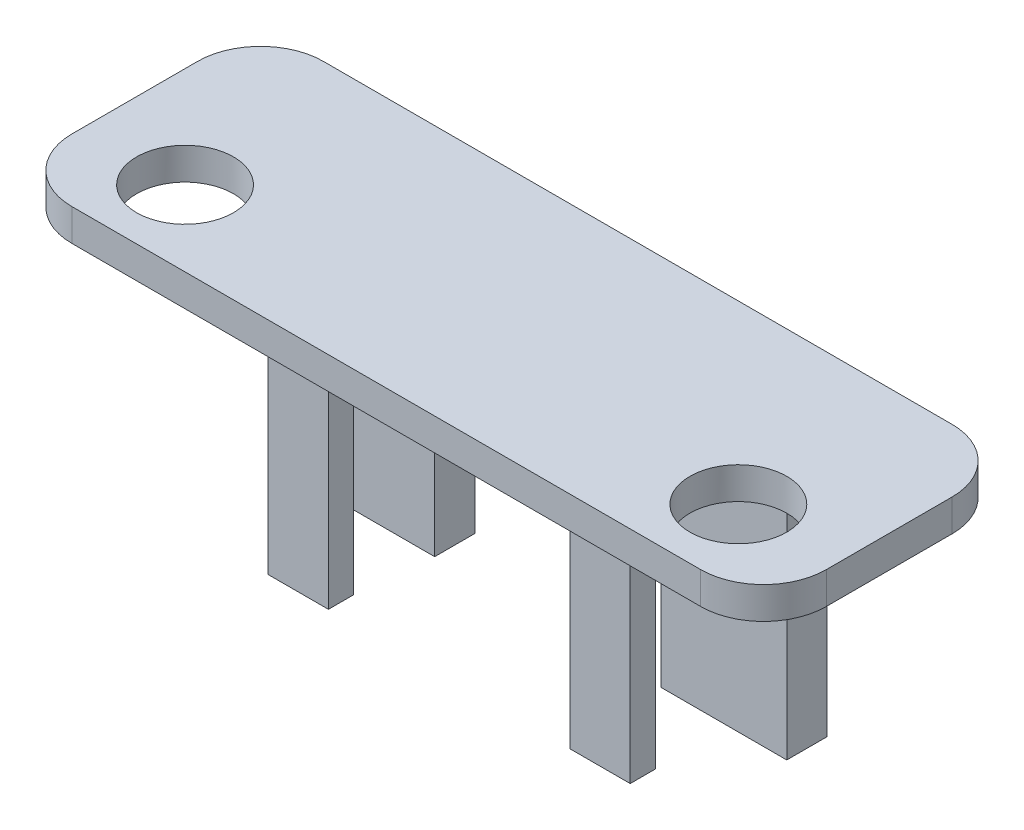
SolidWorks part; units mm, degrees
ref_plane "Front Plane" through (0, 0, 0) normal (0, 0, 1) x (1, 0, 0)
ref_plane "Top Plane" through (0, 0, 0) normal (0, 1, 0) x (1, 0, 0)
ref_plane "Right Plane" through (0, 0, 0) normal (1, 0, 0) x (0, 0, -1)
sketch "Sketch1" plane through (0, 0, 0) normal (0, 1, 0) x (1, 0, 0)
  line L1 (-30, -10) -> (30, -10)
  line L2 (-30, -10) -> (-30, 10)
  line L3 (-30, 10) -> (30, 10)
  line L4 (30, -10) -> (30, 10)
  line L5 (-30, -10) -> (30, 10) construction
  line L6 (-30, 10) -> (30, -10) construction
  point P0 (0, 0)
  dimension "D1" = 20
  dimension "D2" = 60
extrude "Boss-Extrude1" add sketch "Sketch1" along normal blind 2.54
sketch "Sketch2" plane through (0, 2.54, 0) normal (0, 1, 0) x (1, 0, 0)
  line L0 (-25.85, -4) -> (-18.15, -4) construction
  line L3 (0, 0) -> (0, 10) construction
  line L4 (30, 10) -> (-30, 10) construction
  line L5 (18.15, -4) -> (25.85, -4) construction
  line L6 (-30, -10) -> (30, -10) construction
  circle A0 centre (-22, -4) radius 3.85
  circle A1 centre (22, -4) radius 3.85
  dimension "D1" = 7.7
  dimension "D2" = 7.7
  dimension "D5" = 6
  dimension "D3" = 44
  dimension "D4" = 22
extrude "Eyeshaft holes" cut sketch "Sketch2" against normal blind 10
sketch "Sketch3" plane through (0, 0, -10) normal (0, 0, -1) x (-1, 0, 0)
  line L0 (-30, 2.54) -> (30, 2.54) construction
  line L1 (-13.5, 2.54) -> (-19.3221, 2.54)
  line L2 (-13.5, 2.54) -> (-13.5, 0)
  line L3 (-13.5, 0) -> (-19.3221, 0)
  line L4 (-19.3221, 2.54) -> (-19.3221, 0)
  line L5 (-30, 0) -> (30, 0) construction
  line L7 (13.1533, 2.54) -> (12, 2.54)
  line L8 (13.1533, 2.54) -> (13.1533, 0)
  line L9 (13.1533, 0) -> (12, 0)
  line L10 (12, 2.54) -> (12, 0)
  line L12 (-30, 2.54) -> (-30, 0) construction
  line L13 (30, 2.54) -> (30, 0) construction
  dimension "D1" = 16.5
  dimension "D2" = 18
extrude "Boss-Extrude2" [suppressed] add sketch "Sketch3" along normal blind 5
sketch "Sketch4" [suppressed] plane through (0, 0, 0) normal (0, -1, 0) x (1, 0, 0)
  line L0 (-13.1533, -15) -> (-13.1533, -10) construction
  line L1 (-22, -15) -> (-13.1533, -15)
  line L2 (-22, -15) -> (-22, -12.5)
  line L3 (-22, -12.5) -> (-13.1533, -12.5)
  line L4 (-13.1533, -15) -> (-13.1533, -12.5)
  line L5 (23.5, -15) -> (23.5, -10) construction
  line L6 (19.3221, -15) -> (23.5, -15)
  line L7 (19.3221, -15) -> (19.3221, -12.5)
  line L8 (19.3221, -12.5) -> (23.5, -12.5)
  line L9 (23.5, -15) -> (23.5, -12.5)
extrude "Boss-Extrude3" [suppressed] add sketch "Sketch4" along normal blind 15
sketch "Sketch5" plane through (0, 0, 0) normal (0, -1, 0) x (1, 0, 0)
  line L0 (-22, 4) -> (22, 4) construction
  line L10 (-14.4, 3) -> (-9.6, 3)
  line L11 (-14.4, 3) -> (-14.4, 5)
  line L12 (-14.4, 5) -> (-9.6, 5)
  line L13 (-9.6, 3) -> (-9.6, 5)
  line L14 (-14.4, 3) -> (-9.6, 5) construction
  line L15 (-14.4, 5) -> (-9.6, 3) construction
  line L16 (9.6, 3) -> (14.4, 3)
  line L17 (9.6, 3) -> (9.6, 5)
  line L18 (9.6, 5) -> (14.4, 5)
  line L19 (14.4, 3) -> (14.4, 5)
  line L20 (9.6, 3) -> (14.4, 5) construction
  line L21 (9.6, 5) -> (14.4, 3) construction
  point P0 (-12, 4)
  point P5 (12, 4)
  dimension "D1" = 4.8
  dimension "D2" = 2
  dimension "D3" = 10
  dimension "D4" = 10
  dimension "D5" = 4.8
  dimension "D6" = 2
extrude "Front Legs" add sketch "Sketch5" along normal blind 20
fillet "Fillet1" [suppressed] radius 10
sketch "Sketch7" plane through (0, 0, 0) normal (0, -1, 0) x (1, 0, 0)
  line L1 (-19, -6.05) -> (-9, -6.05)
  line L2 (-19, -6.05) -> (-19, -2.85)
  line L3 (-19, -2.85) -> (-9, -2.85)
  line L4 (19, -6.05) -> (19, -2.85)
  line L6 (9, -6.05) -> (9, -2.85)
  line L7 (-9, -6.05) -> (-9, -2.85)
  line L8 (9, -6.05) -> (19, -6.05)
  line L9 (9, -2.85) -> (19, -2.85)
  circle A0 centre (-22, 4) radius 3.85 construction
  circle A1 centre (22, 4) radius 3.85 construction
  dimension "D1" = 6.85
  dimension "D3" = 3
  dimension "D2" = 3
  dimension "D4" = 10.05
  dimension "D5" = 10
  dimension "D6" = 10
extrude "Back legs" add sketch "Sketch7" along normal blind 20
fillet "Fillet2" radius 5 4 edges at (-30, 1.27, -10) (-30, 1.27, 10) (30, 1.27, 10) (30, 1.27, -10)
